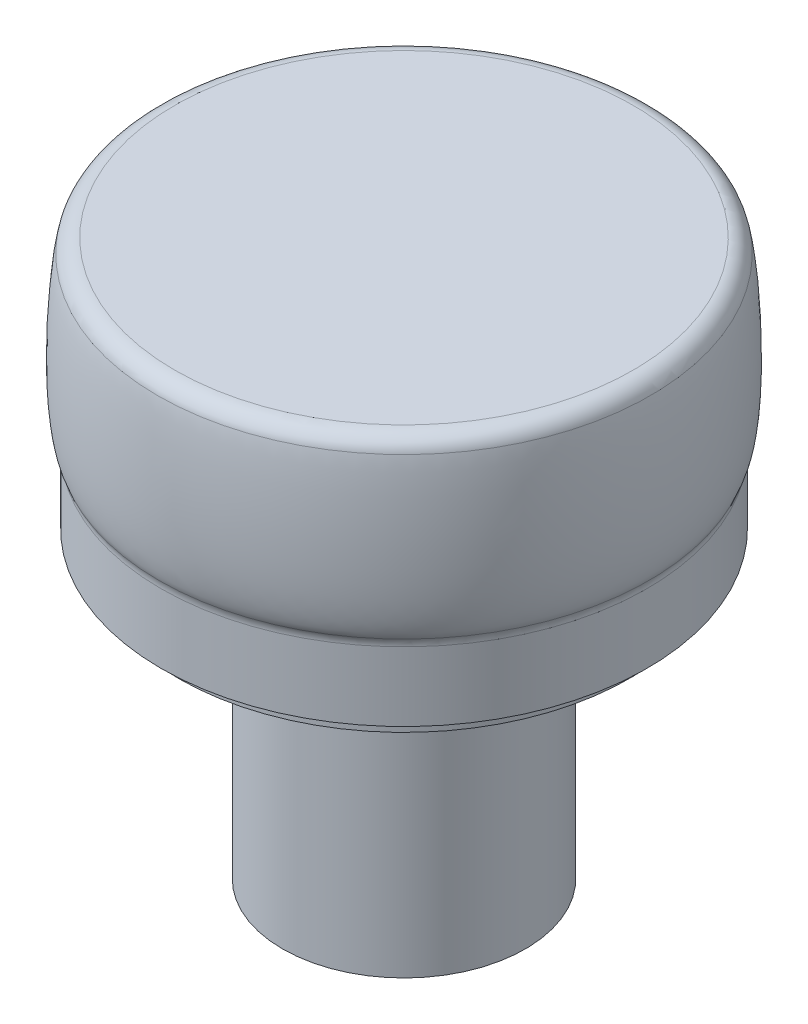
SolidWorks part; units mm, degrees
ref_plane "Plan de face" through (0, 0, 0) normal (0, 0, 1) x (1, 0, 0)
ref_plane "Plan de dessus" through (0, 0, 0) normal (0, 1, 0) x (1, 0, 0)
ref_plane "Plan de droite" through (0, 0, 0) normal (1, 0, 0) x (0, 0, -1)
sketch "Esquisse1" plane through (0, 0, 0) normal (1, 0, 0) x (0, 0, -1)
  line L0 (0, 23.3535) -> (0, -22.5455) construction
  line L1 (0, 18.0202) -> (0, -13.9798)
  line L2 (0, -13.9798) -> (7, -13.9798)
  line L3 (7, -13.9798) -> (7, 2.5202)
  line L4 (7, 2.5202) -> (13, 2.5202)
  line L5 (13, 2.5202) -> (13, 3.5202)
  line L6 (13, 3.5202) -> (14, 3.5202)
  line L7 (14, 3.5202) -> (14, 7.4997)
  line L8 (13.2168, 18.0202) -> (0, 18.0202)
  arc A0 (14.1943, 17.2315) -> (13.2168, 18.0202) centre (13.2168, 17.0202) ccw
  arc A1 (14, 7.4997) -> (14.1152, 7.9656) centre (15, 7.4997) cw
  spline S0 degree 3 poles (14.1943, 17.2315) (14.3244, 16.6294) (14.6929, 13.1537) (14.5804, 8.8491) (14.1152, 7.9656) knots 0.108899 0.108899 0.108899 0.108899 0.358246 0.953924 0.953924 0.953924 0.953924
  point P5 (14.5, 14.5061)
  point P12 (14, 8.8999)
  point P13 (14, 12.5249)
  dimension "D8" = 1
  dimension "D10" = 1
  dimension "D1" = 32
  dimension "D2" = 7
  dimension "D3" = 14
  dimension "D4" = 1
  dimension "D5" = 14.5
  dimension "D6" = 16.5
  dimension "D7" = 1
  dimension "D9" = 3.625
revolve "BASE" add sketch "Esquisse1" angle 360 about L0
